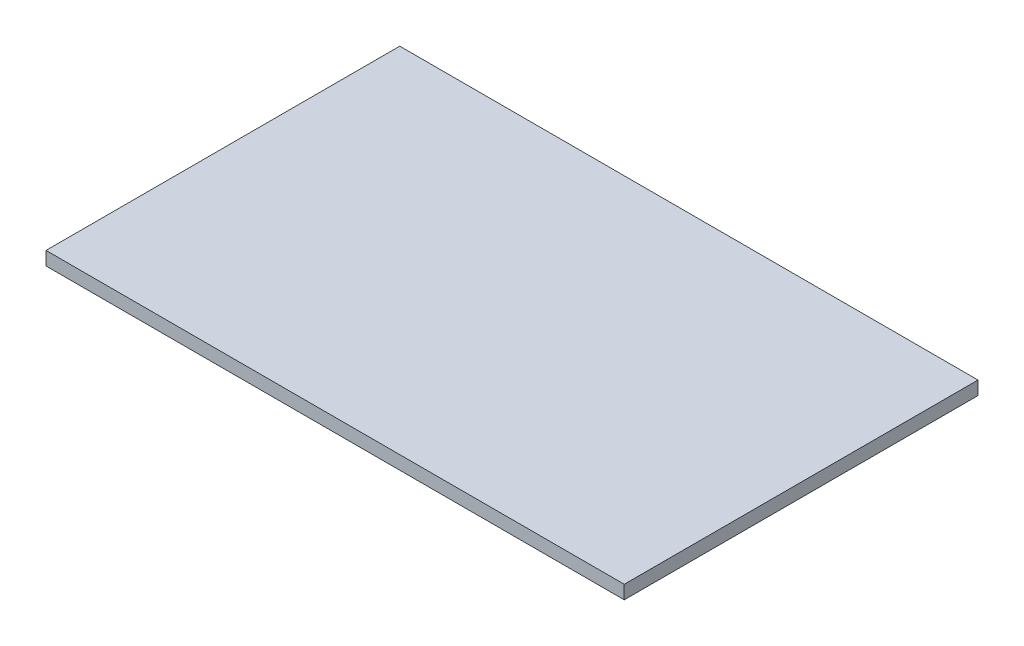
SolidWorks part; units mm, degrees
ref_plane "Front Plane" through (0, 0, 0) normal (0, 0, 1) x (1, 0, 0)
ref_plane "Top Plane" through (0, 0, 0) normal (0, 1, 0) x (1, 0, 0)
ref_plane "Right Plane" through (0, 0, 0) normal (1, 0, 0) x (0, 0, -1)
sketch "Sketch1" plane through (0, 0, 0) normal (0, 1, 0) x (1, 0, 0)
  line L1 (0, 0) -> (85, 0)
  line L2 (0, 0) -> (0, 52)
  line L3 (0, 52) -> (85, 52)
  line L4 (85, 0) -> (85, 52)
  dimension "D1" = 85
  dimension "D2" = 52
extrude "Boss-Extrude1" add sketch "Sketch1" along normal blind 1.9844
sketch "Sketch4" plane through (0, 1.9844, 0) normal (0, 1, 0) x (1, 0, 0)
  line L0 (0, 26) -> (85, 26) construction
  line L1 (0, 3.15) -> (85, 3.15) construction
  line L2 (17, 0) -> (17, 52) construction
  line L3 (0, 0) -> (85, 0) construction
  line L4 (0, 52) -> (0, 0) construction
  line L5 (85, 0) -> (85, 52) construction
  line L6 (85, 52) -> (0, 52) construction
  line L7 (42.4, 0) -> (42.4, 52) construction
  line L8 (67.8, 0) -> (67.8, 52) construction
  circle A0 centre (17, 3.15) radius 1.75
  circle A1 centre (42.4, 3.15) radius 1.75
  circle A2 centre (67.8, 3.15) radius 1.75
  circle A3 centre (67.8, 48.85) radius 1.75
  circle A4 centre (42.4, 48.85) radius 1.75
  circle A5 centre (17, 48.85) radius 1.75
  dimension "D5" = 3.5
  dimension "D1" = 22.85
  dimension "D2" = 17
  dimension "D3" = 25.4
  dimension "D4" = 50.8
